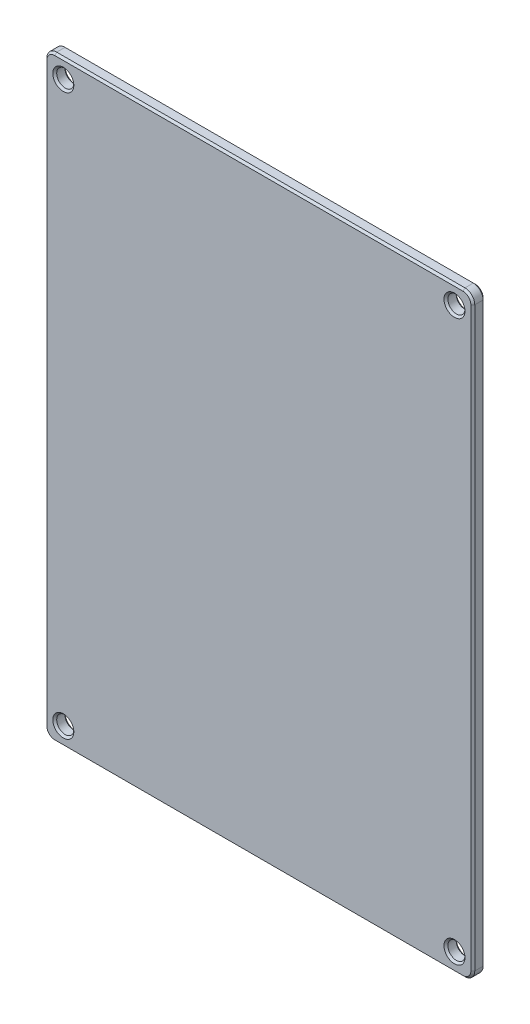
SolidWorks part; units mm, degrees
ref_plane "Ebene vorne" through (0, 0, 0) normal (1, 0, 0) x (0, 1, 0)
ref_plane "Ebene oben" through (0, 0, 0) normal (0, 0, 1) x (0, 1, 0)
ref_plane "Ebene rechts" through (0, 0, 0) normal (0, 1, 0) x (-1, 0, 0)
sketch "Skizze1" plane through (0, 0, 0) normal (0, 0, 1) x (0, 1, 0)
  line L0 (0, 43.75) -> (0, -43.75) construction
  line L1 (59, -43.75) -> (-59, -43.75)
  line L2 (61, -41.75) -> (61, 41.75)
  line L3 (59, 43.75) -> (-59, 43.75)
  line L4 (-61, -41.75) -> (-61, 41.75)
  line L7 (-61, 0) -> (61, 0) construction
  arc A0 (-59, -43.75) -> (-61, -41.75) centre (-59, -41.75) cw
  arc A1 (59, -43.75) -> (61, -41.75) centre (59, -41.75) ccw
  arc A2 (59, 43.75) -> (61, 41.75) centre (59, 41.75) cw
  arc A3 (-59, 43.75) -> (-61, 41.75) centre (-59, 41.75) ccw
  circle A8 centre (-57.25, 40) radius 1.75
  circle A9 centre (57.25, 40) radius 1.75
  circle A10 centre (57.25, -40) radius 1.75
  circle A11 centre (-57.25, -40) radius 1.75
  point P0 (0, 0)
  point P1 (0, 0)
  dimension "D1" = 2
  dimension "D4" = 114.5
  dimension "D5" = 80
  dimension "D6" = 3.5
  dimension "D2" = 87.5
  dimension "D3" = 122
extrude "Aufsatz-Linear austragen1" add sketch "Skizze1" along normal blind 2.5
chamfer "Fase1" distance 0.4 angle 45 24 edges at (43.75, 0, 2.5) (43.1642, -60.4142, 2.5) (0, -61, 2.5) (-43.1642, -60.4142, 2.5) (-43.75, 0, 2.5) (-43.1642, 60.4142, 2.5) (0, 61, 2.5) (43.1642, 60.4142, 2.5) (-41.75, 57.25, 2.5) (-38.25, -57.25, 2.5) (41.75, 57.25, 2.5) (38.25, -57.25, 2.5) (43.1642, 60.4142, 0) (0, 61, 0) (-43.1642, 60.4142, 0) (-43.75, 0, 0) (-43.1642, -60.4142, 0) (0, -61, 0) (43.1642, -60.4142, 0) (43.75, 0, 0) (38.25, -57.25, 0) (-38.25, -57.25, 0) (-41.75, 57.25, 0) (41.75, 57.25, 0)
